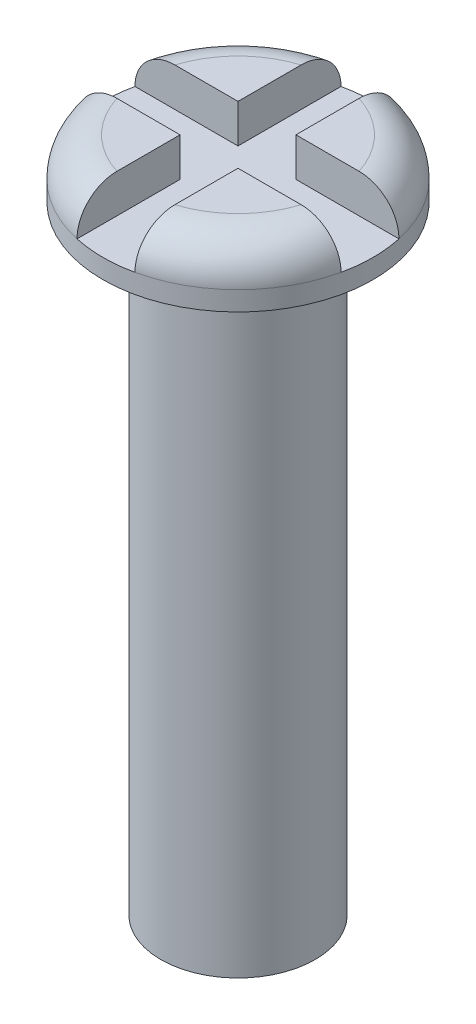
SolidWorks part; units mm, degrees
ref_plane "前视基准面" through (0, 0, 0) normal (0, 0, 1) x (1, 0, 0)
ref_plane "上视基准面" through (0, 0, 0) normal (0, 1, 0) x (1, 0, 0)
ref_plane "右视基准面" through (0, 0, 0) normal (1, 0, 0) x (0, 0, -1)
sketch "草图1" plane through (0, 0, 0) normal (0, 1, 0) x (1, 0, 0)
  circle A0 centre (0, 0) radius 1
  dimension "D1" = 2
extrude "拉伸1" add sketch "草图1" along normal blind 8
sketch "草图2" plane through (0, 8, 0) normal (0, 1, 0) x (-1, 0, 0)
  circle A0 centre (0, 0) radius 1.75
  dimension "D1" = 3.5
extrude "拉伸2" add sketch "草图2" along normal blind 0.75
fillet "圆角1" radius 0.5 1 edges at (0, 8.75, 1.75)
sketch "草图3" plane through (0, 8.75, 0) normal (0, 1, 0) x (-1, 0, 0)
  line L0 (4.0624, 0) -> (-4.2778, 0) construction
  line L1 (0, -3.5166) -> (0, 3.738) construction
  line L3 (3.5023, -0.375) -> (-3.5023, -0.375)
  line L4 (3.5023, -0.375) -> (3.5023, 0.375)
  line L5 (3.5023, 0.375) -> (-3.5023, 0.375)
  line L6 (-3.5023, -0.375) -> (-3.5023, 0.375)
  dimension "D1" = 0.75
extrude "切除-拉伸1" cut sketch "草图3" against normal blind 0.5
sketch "草图4" plane through (0, 8.75, 0) normal (0, 1, 0) x (-1, 0, 0)
  line L0 (0, -3.8639) -> (0, 3.6765) construction
  line L1 (1.7727, 0) -> (-1.7019, 0) construction
  line L2 (0.375, -1.875) -> (-0.375, -1.875)
  line L3 (0.375, -1.875) -> (0.375, 1.875)
  line L4 (0.375, 1.875) -> (-0.375, 1.875)
  line L5 (-0.375, -1.875) -> (-0.375, 1.875)
  dimension "D1" = 0.75
  dimension "D2" = 3.75
extrude "切除-拉伸2" cut sketch "草图4" against normal blind 0.5
